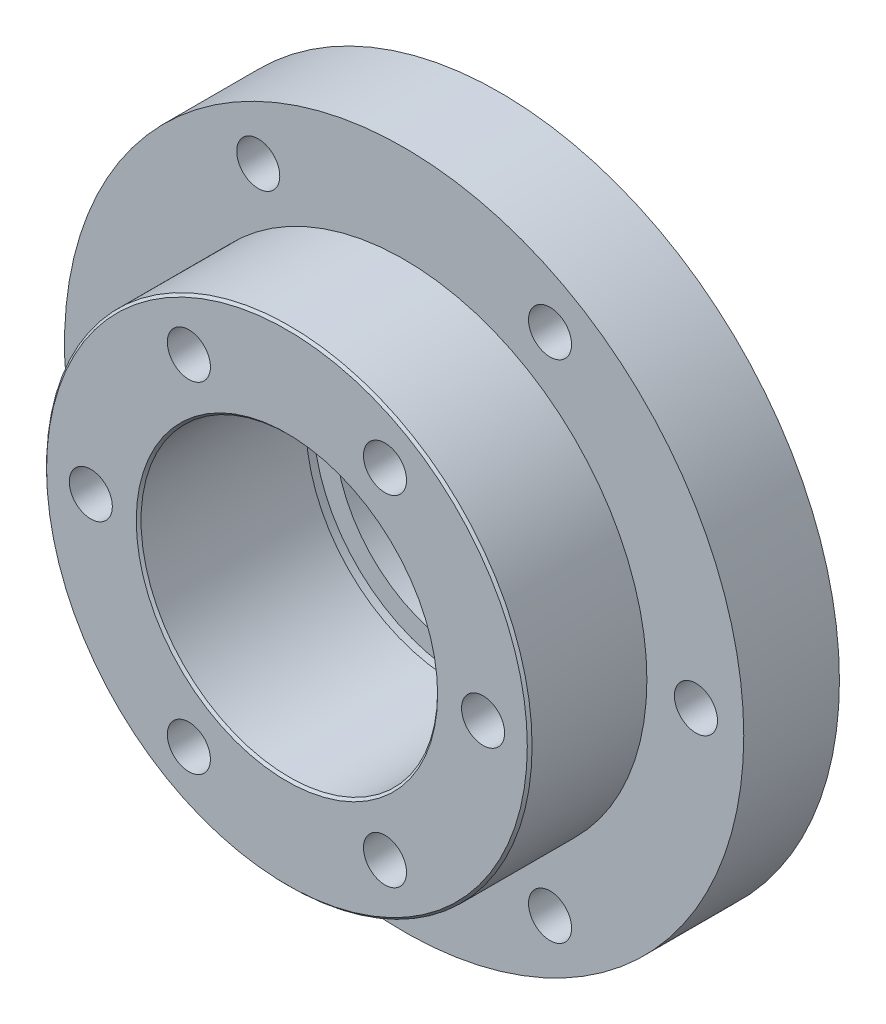
SolidWorks part; units mm, degrees
ref_plane "前视基准面" through (0, 0, 0) normal (0, 0, 1) x (1, 0, 0)
ref_plane "上视基准面" through (0, 0, 0) normal (0, 1, 0) x (1, 0, 0)
ref_plane "右视基准面" through (0, 0, 0) normal (1, 0, 0) x (0, 0, -1)
other "Configuration Table"
sketch "草图1" plane through (0, 0, 0) normal (0, 0, 1) x (1, 0, 0)
  circle A0 centre (0, 0) radius 71
  dimension "D1" = 142
extrude "凸台-拉伸1" add sketch "草图1" along normal blind 20
sketch "草图2" plane through (0, 0, 20) normal (0, 0, 1) x (1, 0, 0)
  circle A0 centre (0, 0) radius 50.75
  dimension "D1" = 101.5
extrude "凸台-拉伸2" add sketch "草图2" along normal blind 24.5
sketch "草图4" plane through (0, 0, 44.5) normal (0, 0, 1) x (1, 0, 0)
  circle A0 centre (0, 0) radius 31
  dimension "D1" = 62
extrude "切除-拉伸1" cut sketch "草图4" against normal blind 35
chamfer "倒角1" distance 0.5 angle 45 2 edges at (31, 0, 44.5) (50.75, 0, 44.5)
sketch "草图5" plane through (0, 0, 0) normal (0, 0, -1) x (-1, 0, 0)
  circle A0 centre (0, 0) radius 27
  dimension "D1" = 54
extrude "切除-拉伸2" cut sketch "草图5" against normal blind 8
sketch "草图6" plane through (0, 0, 9.5) normal (0, 0, 1) x (1, 0, 0)
  circle A0 centre (0, 0) radius 31.5
  dimension "D1" = 63
extrude "切除-拉伸3" cut sketch "草图6" against normal blind 2
sketch "草图7" plane through (0, 0, 20) normal (0, 0, 1) x (1, 0, 0)
  line L0 (-74.74, 0) -> (89.1936, 0) construction
  circle A0 centre (0, 0) radius 61 construction
  circle A1 centre (-61, 0) radius 4.5
  circle A2 centre (-30.5, 52.8275) radius 4.5
  circle A3 centre (30.5, 52.8275) radius 4.5
  circle A4 centre (61, 0) radius 4.5
  circle A5 centre (30.5, -52.8275) radius 4.5
  circle A6 centre (-30.5, -52.8275) radius 4.5
  point P20 (0, 0)
  dimension "D1" = 122
  dimension "D2" = 9
  dimension "D3" = 6
extrude "切除-拉伸4" cut sketch "草图7" against normal up to next
sketch "草图8" plane through (0, 0, 0) normal (0, 0, -1) x (-1, 0, 0)
  circle A0 centre (-41, 0) radius 4
  circle A1 centre (0, 0) radius 71 construction
  dimension "D2" = 8
  dimension "D1" = 41
extrude "切除-拉伸5" cut sketch "草图8" against normal blind 10
sketch "草图9" plane through (0, 0, 44.5) normal (0, 0, 1) x (1, 0, 0)
  line L0 (47.027, 0) -> (-47.027, 0) construction
  line L1 (0, -58.9727) -> (0, 58.9727) construction
  circle A1 centre (41, 0) radius 4.5
  circle A2 centre (20.5, -35.507) radius 4.5
  circle A3 centre (-20.5, -35.507) radius 4.5
  circle A4 centre (-41, 0) radius 4.5
  circle A5 centre (-20.5, 35.507) radius 4.5
  circle A6 centre (20.5, 35.507) radius 4.5
  point P6 (0, 0)
  point P9 (0, 0)
  point P24 (0, 0)
  dimension "D2" = 9
  dimension "D3" = 6
extrude "切除-拉伸6" cut sketch "草图9" against normal blind 12
